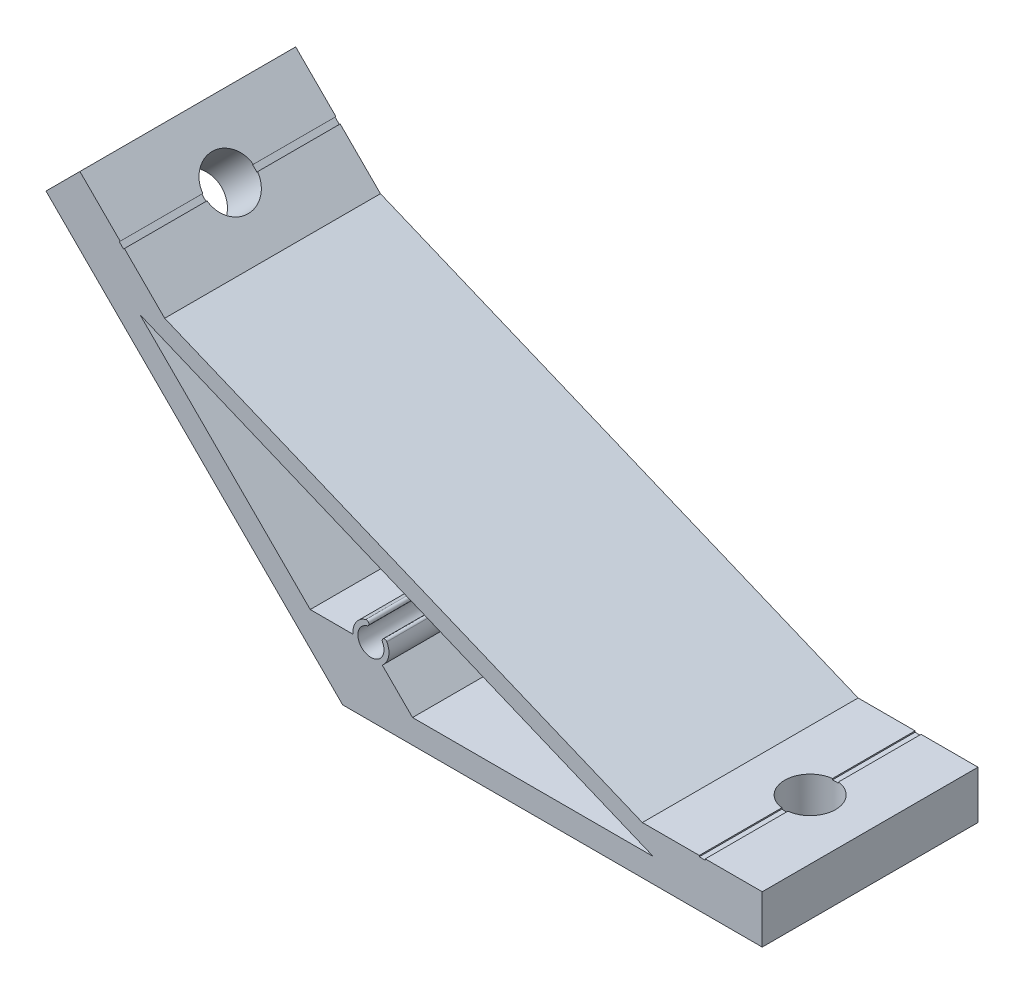
SolidWorks part; units mm, degrees
material "1060 合金"
ref_plane "前视基准面" through (0, 0, 0) normal (0, 0, 1) x (1, 0, 0)
ref_plane "上视基准面" through (0, 0, 0) normal (0, 1, 0) x (1, 0, 0)
ref_plane "右视基准面" through (0, 0, 0) normal (1, 0, 0) x (0, 0, -1)
sketch "草图1" plane through (0, 0, 0) normal (0, 0, 1) x (1, 0, 0)
  line L0 (0, 0) -> (70, 0)
  line L1 (0, 0) -> (-49.4975, 49.4975)
  line L2 (-49.4975, 49.4975) -> (-43.8406, 55.1543)
  line L3 (-43.8406, 55.1543) -> (-29.6985, 41.0122)
  line L4 (-29.6985, 41.0122) -> (50, 8)
  line L5 (50, 8) -> (70, 8)
  line L6 (70, 8) -> (70, 0)
  line L7 (-33.8121, 39.4689) -> (-5.4142, 11.0711)
  line L8 (11.6569, 4) -> (51.8175, 4)
  line L9 (51.8175, 4) -> (-33.8121, 39.4689)
  line L10 (-5.4142, 11.0711) -> (1.7354, 11.0711)
  line L11 (6.6013, 9.0556) -> (11.6569, 4)
  line L12 (0, 0) -> (21.6287, 52.2162) construction
  line L13 (3.9633, 13.8686) -> (7.0041, 12.609) construction
  arc A0 (3.8438, 14.2607) -> (1.7354, 11.0711) centre (4.7183, 11.391) ccw
  arc A1 (4.0828, 13.4764) -> (6.6422, 12.4162) centre (4.7183, 11.391) ccw
  arc A2 (4.0828, 13.4764) -> (3.8438, 14.2607) centre (3.9633, 13.8686) ccw
  arc A3 (7.3659, 12.8019) -> (6.6422, 12.4162) centre (7.0041, 12.609) ccw
  arc A4 (6.6013, 9.0556) -> (7.3659, 12.8019) centre (4.7183, 11.391) ccw
  dimension "D14" = 6
  dimension "D16" = 4.36
  dimension "D1" = 135
  dimension "D2" = 8
  dimension "D3" = 8
  dimension "D4" = 70
  dimension "D5" = 70
  dimension "D6" = 20
  dimension "D7" = 20
  dimension "D8" = 4
  dimension "D9" = 4
  dimension "D10" = 3
  dimension "D11" = 67.5
  dimension "D12" = 135
extrude "凸台-拉伸1" add sketch "草图1" along normal blind 36
sketch "草图2" plane through (0, 8, 0) normal (0, 1, 0) x (1, 0, 0)
  line L0 (70, -36) -> (70, 0) construction
  line L1 (70, -36) -> (50, -36) construction
  circle A0 centre (60, -18) radius 4.25
  dimension "D1" = 8.5
  dimension "D2" = 10
  dimension "D3" = 18
extrude "切除-拉伸1" cut sketch "草图2" against normal up to next
sketch "草图3" plane through (5.6569, 5.6569, 0) normal (0.7071, 0.7071, 0) x (0, 0, -1)
  line L0 (-36, 50) -> (-36, 70) construction
  line L1 (-36, 70) -> (0, 70) construction
  circle A0 centre (-18, 60) radius 4.25
  dimension "D1" = 8.5
  dimension "D2" = 18
  dimension "D3" = 10
extrude "切除-拉伸2" cut sketch "草图3" against normal up to next and the other way through all
sketch "草图4" plane through (0, 8, 0) normal (0, 1, 0) x (1, 0, 0)
  line L0 (70, -36) -> (50, -36) construction
  line L1 (59.5, -36) -> (60.5, -36)
  line L2 (59.5, -36) -> (59.5, 0)
  line L3 (59.5, 0) -> (60.5, 0)
  line L4 (60.5, -36) -> (60.5, 0)
  line L5 (70, 0) -> (50, 0) construction
  line L6 (60, -36) -> (60, 0) construction
  line L7 (70, -36) -> (70, 0) construction
  dimension "D1" = 10
  dimension "D2" = 0.5
extrude "切除-拉伸3" cut sketch "草图4" against normal blind 0.2
sketch "草图5" plane through (5.6569, 5.6569, 0) normal (0.7071, 0.7071, 0) x (0, 0, -1)
  line L0 (-36, 60) -> (0, 60) construction
  line L1 (-36, 50) -> (-36, 70) construction
  line L2 (0, 50) -> (0, 70) construction
  line L4 (-36, 60.5) -> (0, 60.5)
  line L5 (-36, 60.5) -> (-36, 59.5)
  line L6 (-36, 59.5) -> (0, 59.5)
  line L7 (0, 60.5) -> (0, 59.5)
  dimension "D1" = 0.5
  dimension "D2" = 0.5
extrude "切除-拉伸4" cut sketch "草图5" against normal blind 0.2
